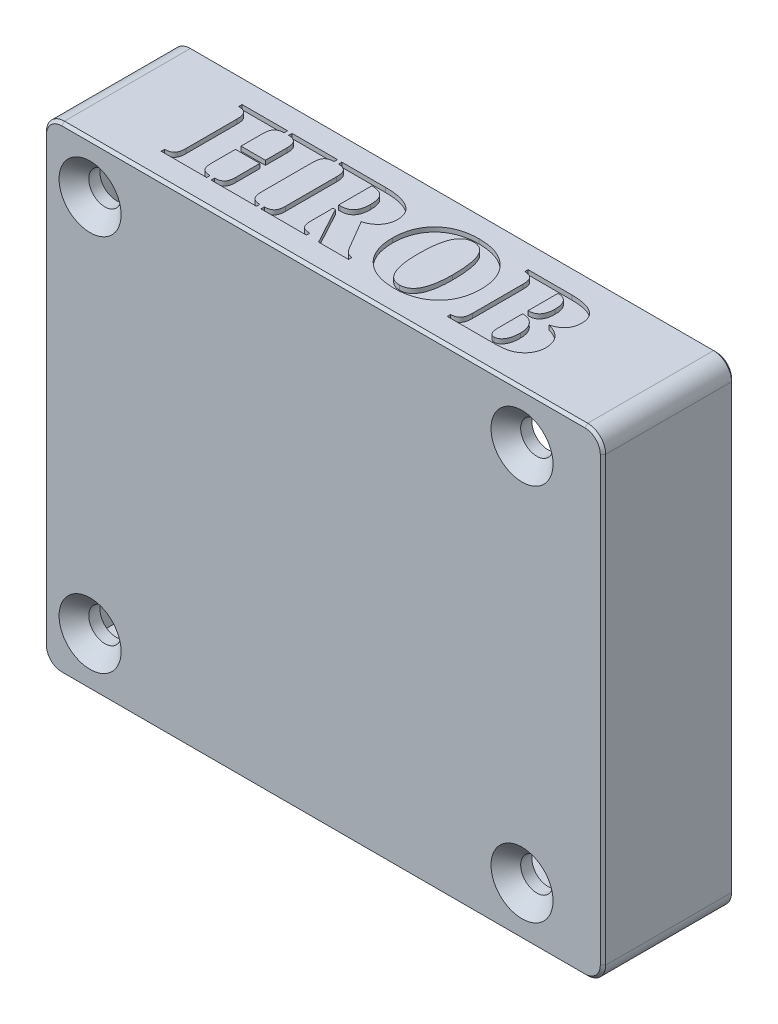
SolidWorks part; units mm, degrees
ref_plane "Ebene vorne" through (0, 0, 0) normal (0, 0, 1) x (1, 0, 0)
ref_plane "Ebene oben" through (0, 0, 0) normal (0, 1, 0) x (1, 0, 0)
ref_plane "Ebene rechts" through (0, 0, 0) normal (1, 0, 0) x (0, 0, -1)
sketch "Skizze1" plane through (0, 0, 0) normal (0, 0, 1) x (1, 0, 0)
  line L0 (-1.85, 51.35) -> (60.35, 51.35)
  line L1 (0, 0) -> (58.5, 0)
  line L2 (0, 0) -> (0, 49.5)
  line L3 (0, 49.5) -> (58.5, 49.5)
  line L4 (58.5, 0) -> (58.5, 49.5)
  line L5 (60.35, -1.85) -> (60.35, 51.35)
  line L6 (-1.85, -1.85) -> (60.35, -1.85)
  line L7 (-1.85, -1.85) -> (-1.85, 51.35)
  dimension "D1" = 58.5
  dimension "D2" = 49.5
  dimension "D3" = 1.85
extrude "Aufsatz-Linear austragen1" add sketch "Skizze1" along normal blind 13.2
sketch "Skizze2" plane through (0, 0, 13.2) normal (0, 0, 1) x (1, 0, 0)
  line L1 (-1.85, 51.35) -> (60.35, 51.35)
  line L2 (-1.85, 51.35) -> (-1.85, -1.85)
  line L3 (-1.85, -1.85) -> (60.35, -1.85)
  line L4 (60.35, 51.35) -> (60.35, -1.85)
extrude "Aufsatz-Linear austragen2" add sketch "Skizze2" along normal blind 1.4
sketch "Skizze3" plane through (0, 0, 13.2) normal (0, 0, -1) x (-1, 0, 0)
  line L0 (-29.25, 49.5) -> (-29.25, 0) construction
  line L1 (-58.5, 49.5) -> (-46.5, 49.5)
  line L2 (-58.5, 49.5) -> (-58.5, 39.5)
  line L3 (-58.5, 39.5) -> (-46.5, 39.5)
  line L4 (-46.5, 49.5) -> (-46.5, 39.5)
  line L5 (-58.5, 49.5) -> (0, 49.5) construction
  line L6 (0, 0) -> (-58.5, 0) construction
  line L7 (-29.25, 24.75) -> (0, 24.75) construction
  line L8 (0, 49.5) -> (0, 0) construction
  line L9 (0, 39.5) -> (-12, 39.5)
  line L10 (-12, 49.5) -> (-12, 39.5)
  line L11 (0, 49.5) -> (-12, 49.5)
  line L12 (0, 49.5) -> (0, 39.5)
  line L13 (0, 0) -> (0, 10)
  line L14 (0, 0) -> (-12, 0)
  line L15 (-12, 0) -> (-12, 10)
  line L16 (0, 10) -> (-12, 10)
  line L17 (-58.5, 10) -> (-46.5, 10)
  line L18 (-46.5, 0) -> (-46.5, 10)
  line L19 (-58.5, 0) -> (-46.5, 0)
  line L20 (-58.5, 0) -> (-58.5, 10)
  dimension "D1" = 12
  dimension "D2" = 10
extrude "Aufsatz-Linear austragen3" add sketch "Skizze3" along normal blind 1.5
sketch "Skizze4" plane through (0, 0, 11.7) normal (0, 0, -1) x (-1, 0, 0)
  circle A0 centre (-51.3445, 45.785) radius 1.65
  circle A1 centre (-3.3045, 45.785) radius 1.65
  circle A2 centre (-3.3045, 3.715) radius 1.65
  circle A3 centre (-51.3445, 3.715) radius 1.65
  dimension "D1" = 3.3
extrude "Schnitt-Linear austragen1" cut sketch "Skizze4" against normal through all
chamfer "Fase1" [suppressed] distance 1.5 angle 45
fillet "Verrundung1" radius 2 4 edges at (60.35, 51.35, 7.3) (-1.85, 51.35, 7.3) (-1.85, -1.85, 7.3) (60.35, -1.85, 7.3)
sketch "Skizze6" plane through (0, 0, 14.6) normal (0, 0, 1) x (1, 0, 0)
  text T0 "HROB" font "Copperplate Gothic Bold" height 12
extrude "Schnitt-Linear austragen3" [suppressed] cut sketch "Skizze6" against normal blind 0.2
chamfer "Fase3" distance 0.3 angle 45 16 edges at (-1.85, 24.75, 0) (-1.2642, -1.2642, 0) (-1.2642, 50.7642, 0) (29.25, -1.85, 0) (29.25, 51.35, 0) (59.7642, -1.2642, 0) (59.7642, 50.7642, 0) (60.35, 24.75, 0) (-1.85, 24.75, 14.6) (-1.2642, -1.2642, 14.6) (-1.2642, 50.7642, 14.6) (29.25, -1.85, 14.6) (29.25, 51.35, 14.6) (59.7642, -1.2642, 14.6) (59.7642, 50.7642, 14.6) (60.35, 24.75, 14.6)
hole_wizard "Formsenkung für M3 Senkschraube mit Schlitz/Kreuzschlitz2" positions "Skizze9" profile "Skizze10" countersink size "M3" standard "DIN" end condition through all
sketch "Skizze9" plane through (0, 0, 14.6) normal (0, 0, 1) x (1, 0, 0)
  point P0 (3.3045, 3.715)
  point P3 (3.3045, 45.785)
  point P6 (51.3445, 45.785)
  point P9 (51.3445, 3.715)
sketch "Skizze10" plane through (3.3045, 3.715, 14.6) normal (1, 0, 0) x (0, -1, 0)
  line L0 (0, 0) -> (0, 14.6)
  line L1 (0, 14.6) -> (1.8, 14.6)
  line L2 (1.8, 14.6) -> (1.8, 1.65)
  line L3 (1.8, 1.65) -> (3.45, 0)
  line L5 (3.45, 0) -> (0, 0)
  line L6 (-1.8, 1.65) -> (-3.45, 0) construction
  line L11 (0, -6.35) -> (0, 107.95) construction
  dimension "Bohrerdurchmesser" = 3.6
  dimension "Bohrungstiefe" = 14.6
  dimension "Senkdurchmesser (Oben)" = 6.9
  dimension "Senkwinkel (Oben)" = 90
sketch "Skizze5" plane through (0, 51.35, 0) normal (0, 1, 0) x (1, 0, 0)
  text T0 "HROB" font "Dutch801 XBd BT" height 9
extrude "Schnitt-Linear austragen2" cut sketch "Skizze5" against normal blind 0.5
ref_point "Point1"
ref_point "Point2"
ref_point "Point3"
